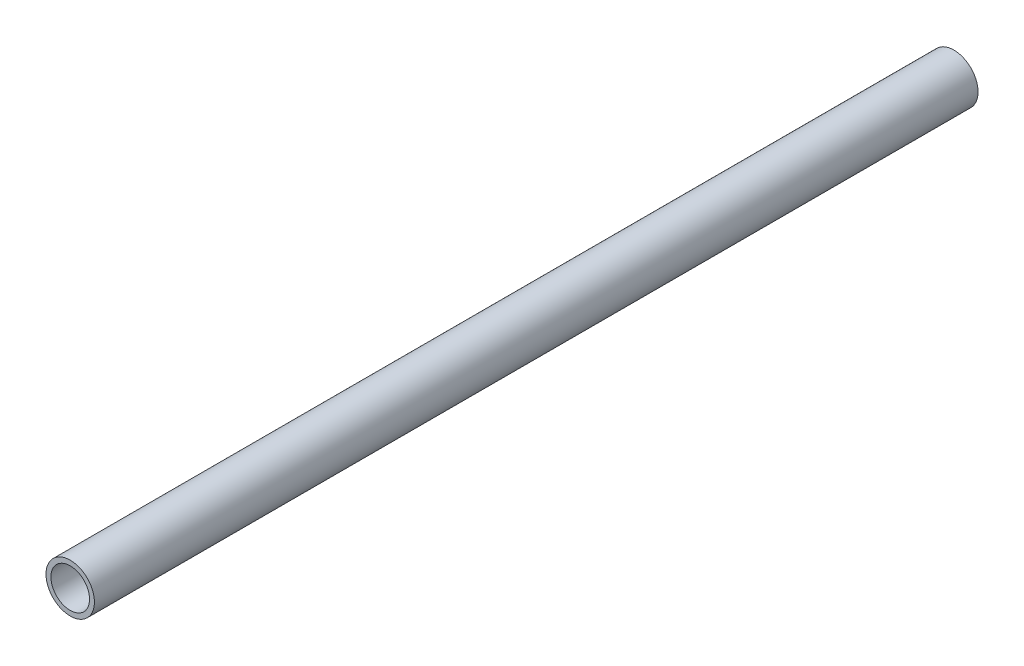
SolidWorks part; units mm, degrees
ref_plane "Front Plane" through (0, 0, 0) normal (0, 0, 1) x (1, 0, 0)
ref_plane "Top Plane" through (0, 0, 0) normal (0, 1, 0) x (1, 0, 0)
ref_plane "Right Plane" through (0, 0, 0) normal (1, 0, 0) x (0, 0, -1)
sketch "Sketch1" plane through (0, 0, 0) normal (0, 0, 1) x (1, 0, 0)
  circle A0 centre (0, 0) radius 13.3223
  circle A1 centre (0, 0) radius 16.7005
  dimension "D1" = 26.6446
  dimension "D2" = 33.401
extrude "Boss-Extrude1" add sketch "Sketch1" along normal blind 609.6
